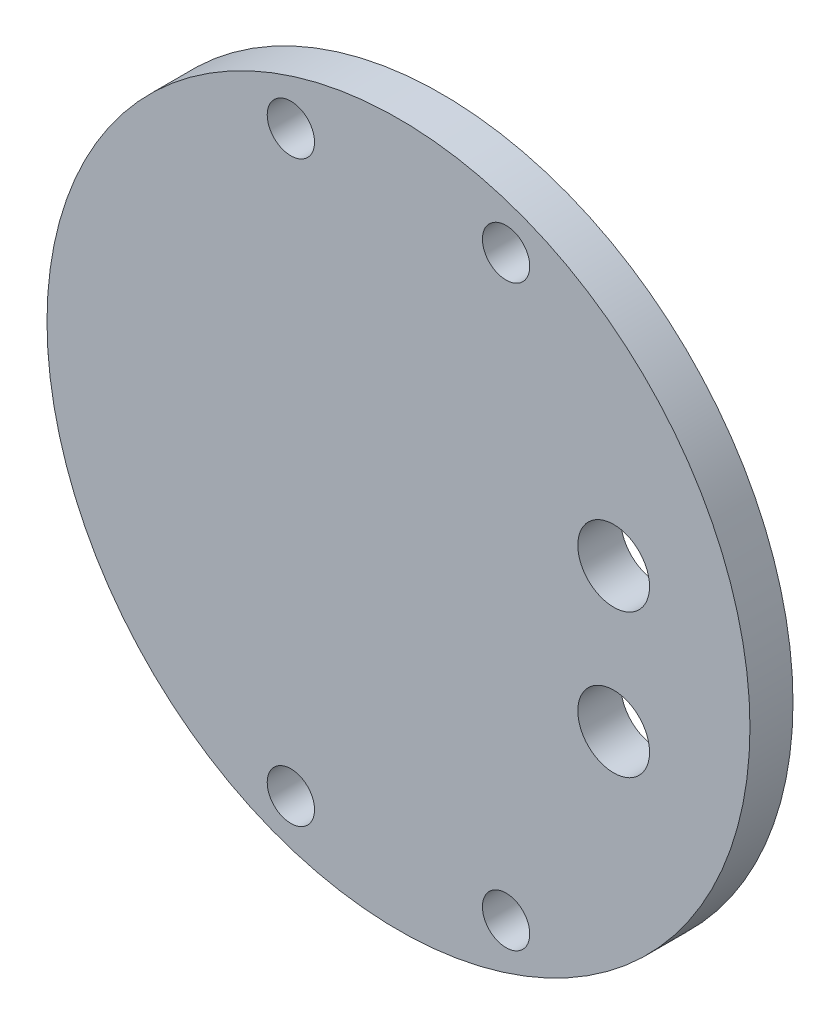
SolidWorks part; units mm, degrees
ref_plane "前视基准面" through (0, 0, 0) normal (0, 0, 1) x (1, 0, 0)
ref_plane "上视基准面" through (0, 0, 0) normal (0, 1, 0) x (1, 0, 0)
ref_plane "右视基准面" through (0, 0, 0) normal (1, 0, 0) x (0, 0, -1)
ref_plane "基准面1" through (0, 0, 6) normal (0, 0, 1) x (1, 0, 0)
sketch "草图1" plane through (0, 0, 6) normal (0, 0, 1) x (1, 0, 0)
  circle A0 centre (15, 40.3) radius 3.3
  circle A1 centre (15, -40.3) radius 3.3
  circle A2 centre (-15, 40.3) radius 3.3
  circle A3 centre (-15, -40.3) radius 3.3
  circle A4 centre (0, 0) radius 49
extrude "凸台-拉伸1" add sketch "草图1" against normal blind 6
sketch "草图2" plane through (0, 0, 6) normal (0, 0, 1) x (1, 0, 0)
  line L1 (30, 0) -> (30, 10) construction
  line L2 (30, 0) -> (30, -10) construction
  line L4 (-30, 0) -> (-30, -10) construction
  line L5 (-30, -10) -> (30, -10) construction
  line L6 (30, 10) -> (-30, 10) construction
  line L7 (-30, 10) -> (-30, 0) construction
  line L9 (21.5, 0) -> (21.5, 10) construction
  line L11 (21.5, 0) -> (21.5, -10) construction
  circle A0 centre (0, 0) radius 30 construction
  circle A1 centre (30, 10) radius 5
  circle A2 centre (30, -10) radius 5
  dimension "D1" = 10
  dimension "D2" = 10
extrude "切除-拉伸1" cut sketch "草图2" against normal through all
